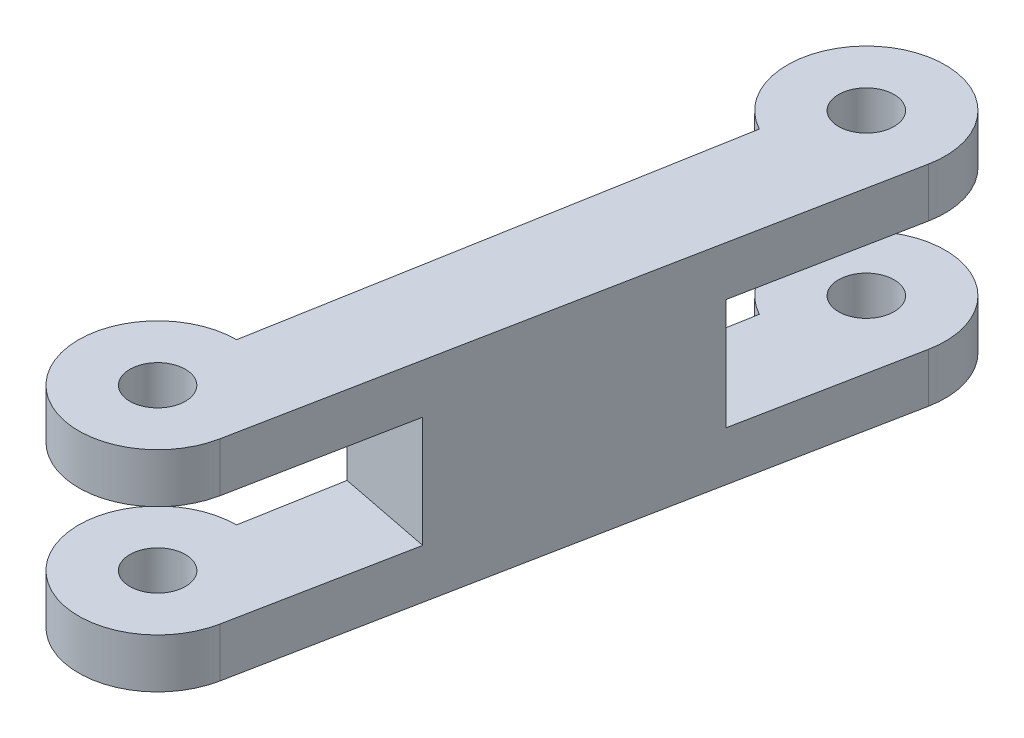
SolidWorks part; units mm, degrees
ref_plane "Front Plane" through (0, 0, 0) normal (0, 0, 1) x (1, 0, 0)
ref_plane "Top Plane" through (0, 0, 0) normal (0, 1, 0) x (1, 0, 0)
ref_plane "Right Plane" through (0, 0, 0) normal (1, 0, 0) x (0, 0, -1)
sketch "Sketch1" plane through (0, 0, 0) normal (0, 1, 0) x (1, 0, 0)
  line L0 (47.2297, 219.0186) -> (732.563, 219.0186) construction
  line L1 (-53.3395, 64.2613) -> (-58.055, 40.2606)
  line L2 (-57.995, 62.0598) -> (-61.195, 44.0775)
  circle A0 centre (-56.4795, 64.8782) radius 1.125
  arc A1 (-53.3395, 64.2613) -> (-57.995, 62.0598) centre (-56.4795, 64.8782) ccw
  circle A2 centre (-61.195, 40.8775) radius 1.125
  arc A3 (-61.195, 44.0775) -> (-58.055, 40.2606) centre (-61.195, 40.8775) ccw
extrude "Boss-Extrude6" add sketch "Sketch1" along normal blind 8.5
sketch "Sketch4" plane through (-63.5134, 0, -12.4787) normal (0.9812, 0, 0.1928) x (0.1928, 0, -0.9812)
  line L0 (28.3131, 8.5) -> (52.7726, 8.5) construction
  line L1 (45.7726, 6.5) -> (63.3434, 6.5)
  line L2 (45.7726, 6.5) -> (45.7726, 2)
  line L3 (45.7726, 2) -> (63.3434, 2)
  line L4 (63.3434, 6.5) -> (63.3434, 2)
  line L5 (52.7726, 8.5) -> (52.7726, 0) construction
  line L6 (28.3131, 8.5) -> (28.3131, 0) construction
  line L7 (35.3131, 6.5) -> (18.5736, 6.5)
  line L8 (35.3131, 6.5) -> (35.3131, 2)
  line L9 (35.3131, 2) -> (18.5736, 2)
  line L10 (18.5736, 6.5) -> (18.5736, 2)
  dimension "D1" = 4.5
  dimension "D2" = 2
  dimension "D3" = 7
  dimension "D4" = 7
extrude "Cut-Extrude2" cut sketch "Sketch4" against normal blind 8.5
